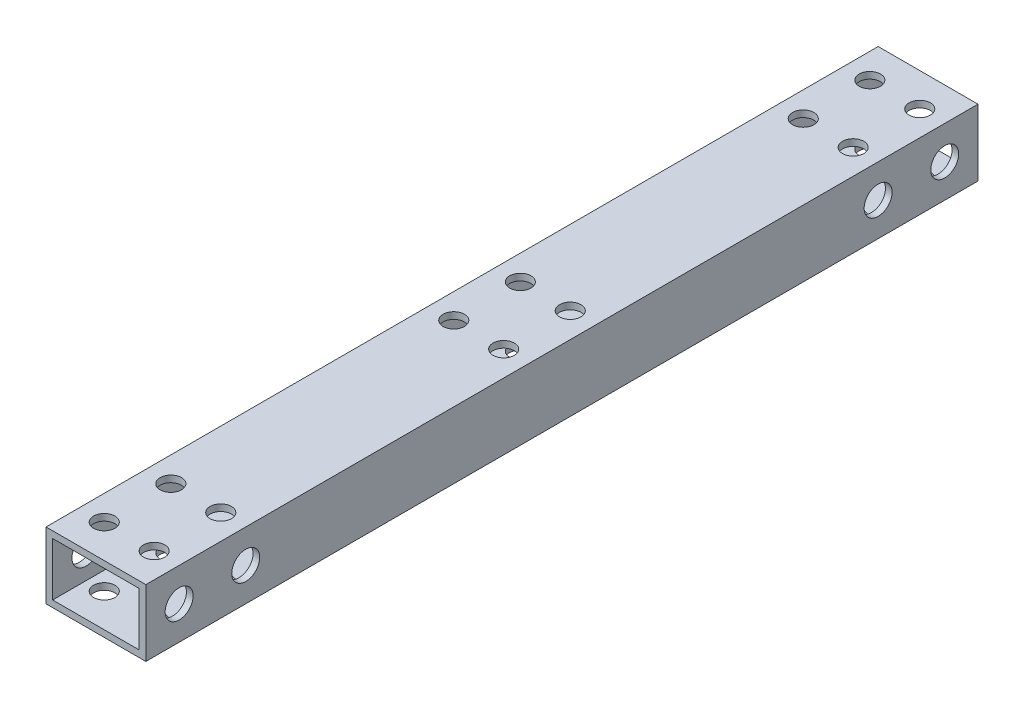
SolidWorks part; units mm, degrees
ref_plane "前视基准面" through (0, 0, 0) normal (0, 0, 1) x (1, 0, 0)
ref_plane "上视基准面" through (0, 0, 0) normal (0, 1, 0) x (1, 0, 0)
ref_plane "右视基准面" through (0, 0, 0) normal (1, 0, 0) x (0, 0, -1)
other "Configuration Table"
sketch "草图1" plane through (0, 0, 0) normal (0, 0, 1) x (1, 0, 0)
  line L1 (0, 0) -> (15, 0)
  line L2 (0, 0) -> (0, -10)
  line L3 (0, -10) -> (15, -10)
  line L4 (15, 0) -> (15, -10)
  dimension "D1" = 15
  dimension "D2" = 10
extrude "拉伸-薄壁1" add sketch "草图1" along normal blind 125 thin
sketch "草图2" plane through (15, 0, 0) normal (1, 0, 0) x (0, 0, -1)
  line L0 (-125, -5) -> (0, -5) construction
  line L3 (-125, -10) -> (-125, 0) construction
  line L4 (0, -10) -> (0, 0) construction
  line L5 (-115, 0) -> (-115, -10) construction
  line L6 (-125, 0) -> (0, 0) construction
  line L7 (-125, -10) -> (0, -10) construction
  line L8 (-62.5, 0) -> (-62.5, -10) construction
  line L9 (-10, 0) -> (-10, -10) construction
  circle A1 centre (-120, -5) radius 2.1
  circle A2 centre (-110, -5) radius 2.1
  circle A3 centre (-15, -5) radius 2.1
  circle A4 centre (-5, -5) radius 2.1
  dimension "D1" = 4.2
  dimension "D2" = 10
  dimension "D3" = 5
extrude "切除-拉伸1" cut sketch "草图2" against normal through all
sketch "草图3" plane through (0, -10, 0) normal (0, -1, 0) x (1, 0, 0)
  line L0 (0, 62.5) -> (15, 62.5) construction
  line L1 (0, 125) -> (0, 0) construction
  line L2 (15, 125) -> (15, 0) construction
  line L3 (7.5, 125) -> (7.5, 0) construction
  line L4 (0, 125) -> (15, 125) construction
  line L5 (0, 0) -> (15, 0) construction
  line L6 (0, 115) -> (15, 115) construction
  line L7 (0, 10) -> (15, 10) construction
  circle A0 centre (3.75, 67.5) radius 1.6
  circle A1 centre (11.25, 67.5) radius 1.6
  circle A2 centre (11.25, 57.5) radius 1.6
  circle A3 centre (3.75, 57.5) radius 1.6
  circle A4 centre (3.75, 120) radius 1.6
  circle A5 centre (11.25, 120) radius 1.6
  circle A6 centre (11.25, 110) radius 1.6
  circle A7 centre (3.75, 110) radius 1.6
  circle A8 centre (3.75, 15) radius 1.6
  circle A9 centre (11.25, 15) radius 1.6
  circle A10 centre (11.25, 5) radius 1.6
  circle A11 centre (3.75, 5) radius 1.6
  dimension "D1" = 3.2
  dimension "D5" = 3.2
  dimension "D2" = 3.75
  dimension "D3" = 5
  dimension "D4" = 10
  dimension "D6" = 3.75
  dimension "D7" = 5
extrude "切除-拉伸2" cut sketch "草图3" against normal through all
